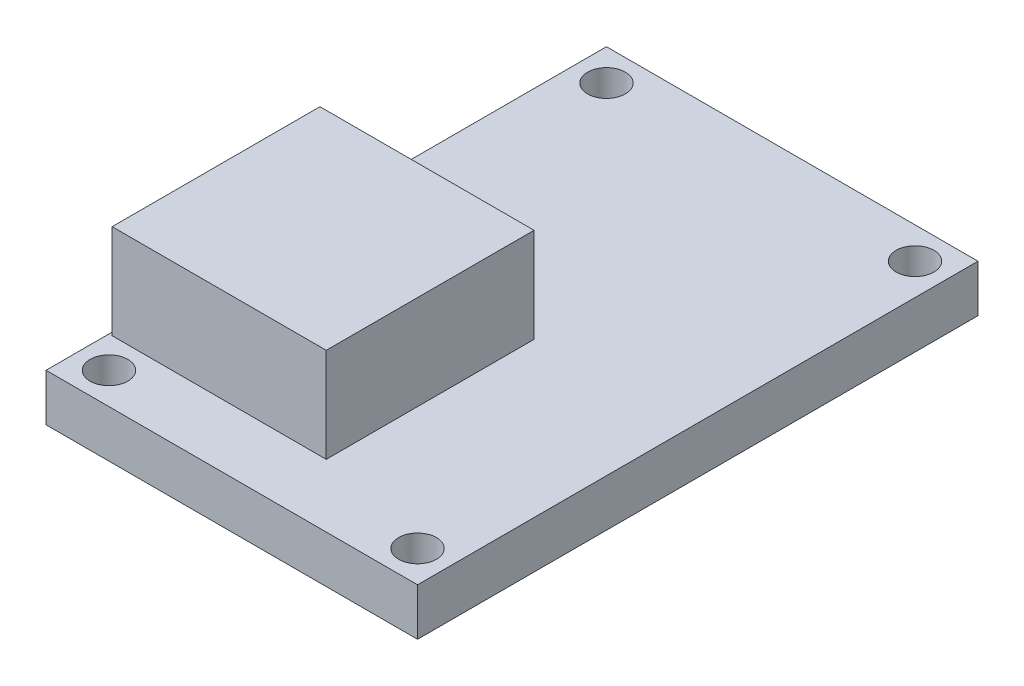
SolidWorks part; units mm, degrees
ref_plane "Front Plane" through (0, 0, 0) normal (0, 0, 1) x (1, 0, 0)
ref_plane "Top Plane" through (0, 0, 0) normal (0, 1, 0) x (1, 0, 0)
ref_plane "Right Plane" through (0, 0, 0) normal (1, 0, 0) x (0, 0, -1)
sketch "Sketch1" plane through (0, 0, 0) normal (0, 1, 0) x (1, 0, 0)
  line L1 (-5.9, -8.9) -> (5.9, -8.9)
  line L2 (-5.9, -8.9) -> (-5.9, 8.9)
  line L3 (-5.9, 8.9) -> (5.9, 8.9)
  line L4 (5.9, -8.9) -> (5.9, 8.9)
  line L5 (-5.9, -8.9) -> (5.9, 8.9) construction
  line L6 (-5.9, 8.9) -> (5.9, -8.9) construction
  circle A0 centre (-4.9, 7.9) radius 0.6
  circle A1 centre (4.9, 7.9) radius 0.6
  circle A2 centre (4.9, -7.9) radius 0.6
  circle A3 centre (-4.9, -7.9) radius 0.6
  point P0 (0, 0)
  dimension "D3" = 1.2
  dimension "D1" = 17.8
  dimension "D2" = 11.8
  dimension "D4" = 1
  dimension "D5" = 1
  dimension "D6" = 1
  dimension "D7" = 1
  dimension "D8" = 1
  dimension "D9" = 1
  dimension "D10" = 1
  dimension "D11" = 1
extrude "Boss-Extrude1" add sketch "Sketch1" along normal blind 1.5
sketch "Sketch2" plane through (0, 1.5, 0) normal (0, 1, 0) x (1, 0, 0)
  line L0 (-5.9, 8.9) -> (-5.9, -8.9) construction
  line L1 (-5.8, -0.3) -> (1, -0.3)
  line L2 (-5.8, -0.3) -> (-5.8, -6.9)
  line L3 (-5.8, -6.9) -> (1, -6.9)
  line L4 (1, -0.3) -> (1, -6.9)
  line L5 (-5.9, -8.9) -> (5.9, -8.9) construction
  dimension "D1" = 6.6
  dimension "D2" = 6.8
  dimension "D3" = 0.1
  dimension "D4" = 2
extrude "Boss-Extrude2" add sketch "Sketch2" along normal blind 3
